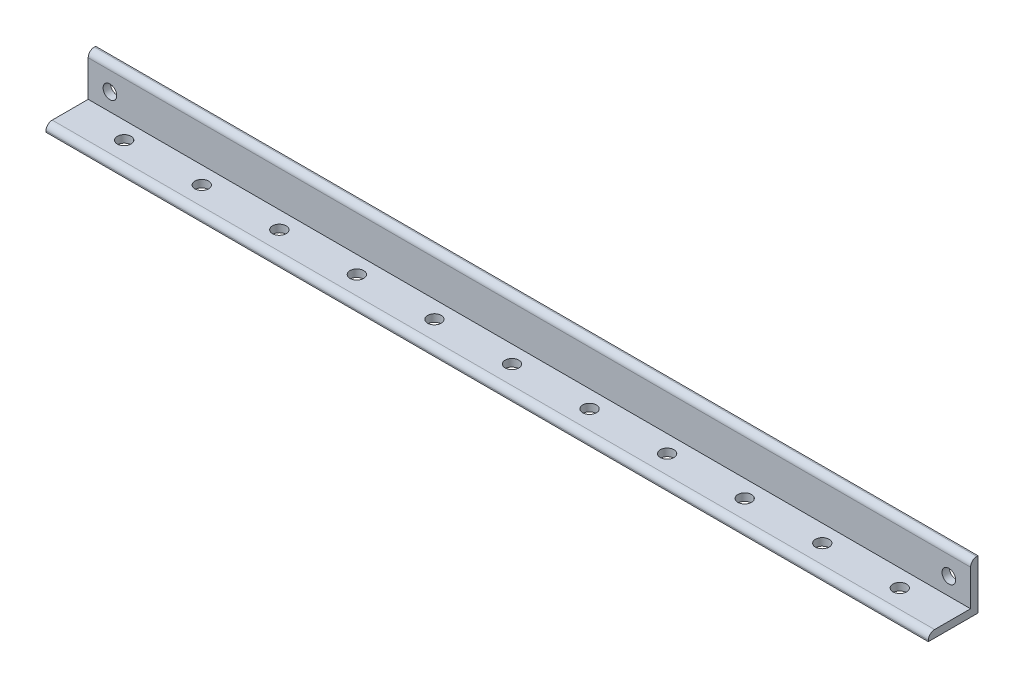
SolidWorks part; units mm, degrees
ref_plane "前视基准面" through (0, 0, 0) normal (0, 0, 1) x (1, 0, 0)
ref_plane "上视基准面" through (0, 0, 0) normal (0, 1, 0) x (1, 0, 0)
ref_plane "右视基准面" through (0, 0, 0) normal (1, 0, 0) x (0, 0, -1)
sketch "草图1" plane through (0, 0, 0) normal (0, 0, 1) x (1, 0, 0)
  line L1 (0, 0) -> (1422, 0)
  line L2 (0, 0) -> (0, 80)
  line L3 (0, 80) -> (1422, 80)
  line L4 (1422, 0) -> (1422, 80)
  dimension "D1" = 1422
  dimension "D2" = 80
extrude "拉伸1" add sketch "草图1" along normal blind 80
sketch "草图3" plane through (0, 0, 0) normal (-1, 0, 0) x (0, 0, 1)
  line L0 (80, 80) -> (80, 0) construction
  line L1 (12, 80) -> (80, 80)
  line L2 (12, 80) -> (12, 12)
  line L3 (12, 12) -> (80, 12)
  line L4 (80, 80) -> (80, 12)
  line L5 (80, 80) -> (0, 80) construction
  line L6 (80, 0) -> (0, 0) construction
  line L7 (0, 80) -> (0, 0) construction
  dimension "D1" = 12
  dimension "D2" = 12
extrude "拉伸2" cut sketch "草图3" against normal through all
fillet "圆角1" radius 10 2 edges at (711, 12, 80) (711, 80, 12)
sketch "草图4" plane through (0, 0, 0) normal (0, 0, -1) x (-1, 0, 0)
  line L0 (-1422, 0) -> (-1422, 80) construction
  line L1 (0, 0) -> (-1422, 0) construction
  circle A0 centre (-1387, 40) radius 11
  dimension "D1" = 35
  dimension "D3" = 22
  dimension "D2" = 40
extrude "拉伸3" cut sketch "草图4" against normal through all
pattern_linear "阵列(线性)1" count 2 spacing 1352 along (-1, 0, 0) of "拉伸3"
sketch "草图5" plane through (0, 0, 0) normal (0, -1, 0) x (1, 0, 0)
  line L0 (0, 80) -> (0, 0) construction
  line L1 (0, 0) -> (1422, 0) construction
  circle A0 centre (86, 40) radius 11
  point P2 (0, 40)
  dimension "D1" = 86
  dimension "D3" = 22
  dimension "D2" = 40
extrude "拉伸4" cut sketch "草图5" against normal through all
pattern_linear "阵列(线性)2" count 11 spacing 125 along (1, 0, 0) of "拉伸4"
